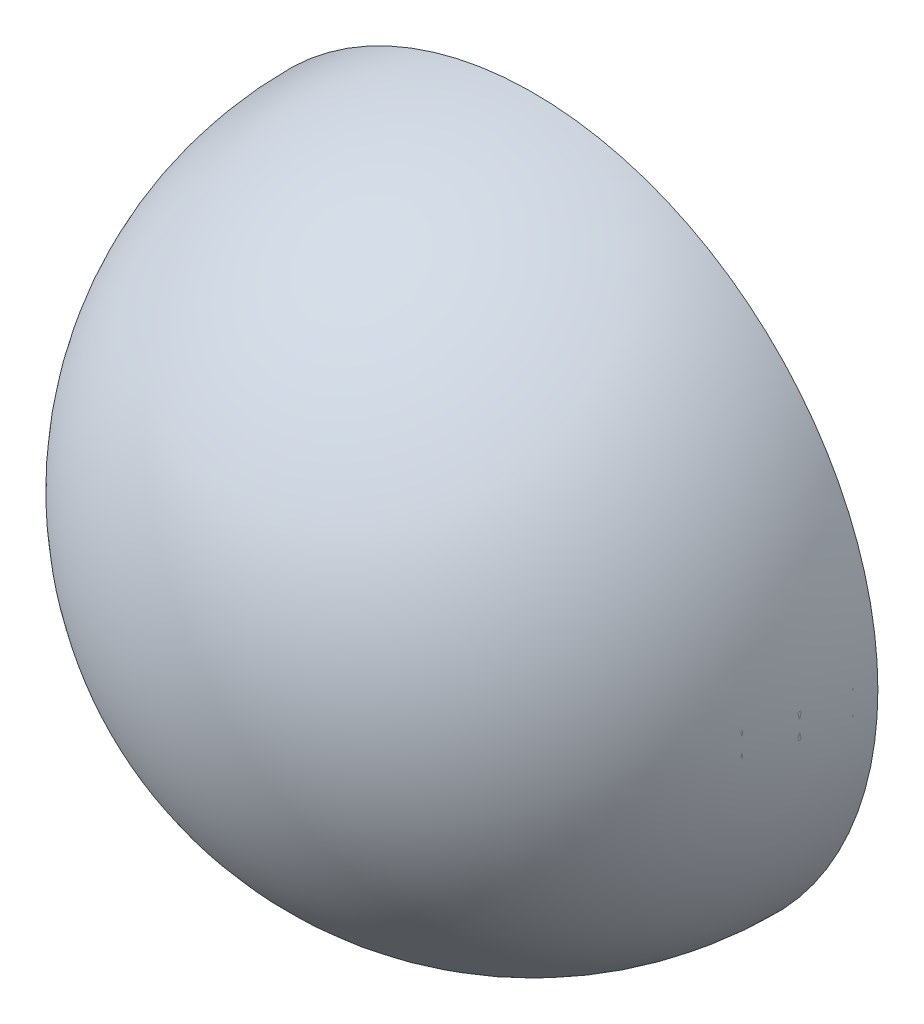
SolidWorks part; units mm, degrees
material "ABS PC"
ref_plane "Front Plane" through (0, 0, 0) normal (0, 0, 1) x (1, 0, 0)
ref_plane "Top Plane" through (0, 0, 0) normal (0, 1, 0) x (1, 0, 0)
ref_plane "Right Plane" through (0, 0, 0) normal (1, 0, 0) x (0, 0, -1)
sketch "Sketch1" plane through (0, 0, 0) normal (0, 0, 1) x (1, 0, 0)
  line L0 (0, -1000) -> (0, 49000) construction
  line L1 (0, 150) -> (0, -150)
  arc A0 (0, 150) -> (0, -150) centre (0, 0) cw
  dimension "D2" = 150
  dimension "D1" = 0
revolve "Revolve1" add sketch "Sketch1" angle 180 about L0
shell "Shell1" thickness 0.1
ref_plane "Plane1" through (0, 0, 370) normal (0, 0, 1) x (1, 0, 0)
sketch "Sketch2" plane through (0, 0, 0) normal (0, 0, 1) x (1, 0, 0)
  point P0 (0, 0)
